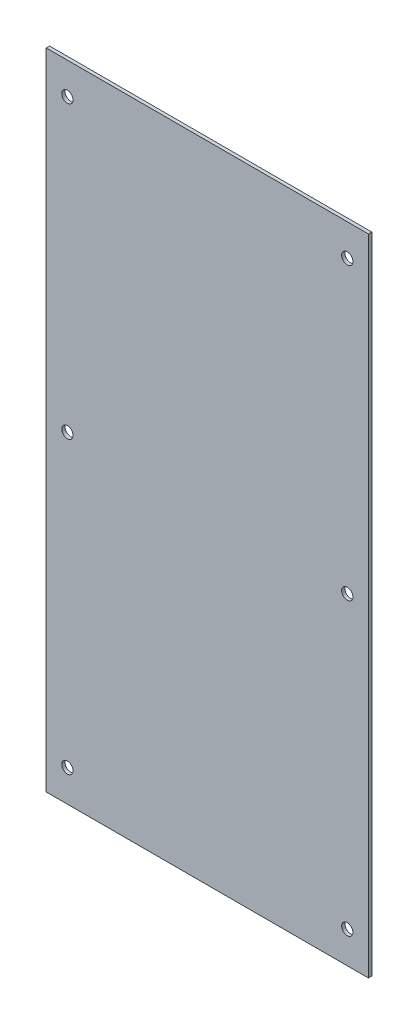
SolidWorks part; units mm, degrees
ref_plane "Front" through (0, 0, 0) normal (0, 0, 1) x (1, 0, 0)
ref_plane "Top" through (0, 0, 0) normal (0, 1, 0) x (1, 0, 0)
ref_plane "Right" through (0, 0, 0) normal (1, 0, 0) x (0, 0, -1)
sketch "Sketch1" plane through (0, 0, 0) normal (0, 0, 1) x (1, 0, 0)
  line L1 (-76.2, -152.4) -> (76.2, -152.4)
  line L2 (-76.2, -152.4) -> (-76.2, 152.4)
  line L3 (-76.2, 152.4) -> (76.2, 152.4)
  line L4 (76.2, -152.4) -> (76.2, 152.4)
  line L5 (-76.2, -152.4) -> (76.2, 152.4) construction
  line L6 (-76.2, 152.4) -> (76.2, -152.4) construction
  point P0 (0, 0)
  dimension "D1" = 304.8
  dimension "D2" = 152.4
extrude "Boss-Extrude1" add sketch "Sketch1" along normal blind 1.5748
sketch "Sketch2" plane through (0, 0, 0) normal (0, 0, -1) x (-1, 0, 0)
  line L0 (-66.2, 152.4) -> (-66.2, -152.4) construction
  line L1 (-76.2, 152.4) -> (76.2, 152.4) construction
  line L2 (76.2, -152.4) -> (-76.2, -152.4) construction
  line L3 (-76.2, -152.4) -> (-76.2, 152.4) construction
  line L4 (-76.2, 0) -> (76.2, 0) construction
  line L5 (76.2, 152.4) -> (76.2, -152.4) construction
  line L6 (0, 0) -> (0, -152.4) construction
  circle A0 centre (-66.2, 137.4) radius 2.665
  circle A1 centre (-66.2, -137.4) radius 2.665
  circle A2 centre (-66.2, 0) radius 2.665
  circle A3 centre (66.2, -137.4) radius 2.665
  circle A4 centre (66.2, 0) radius 2.665
  circle A5 centre (66.2, 137.4) radius 2.665
  dimension "D2" = 15
  dimension "D3" = 5.33
  dimension "D1" = 10
extrude "Cut-Extrude1" cut sketch "Sketch2" against normal up to next
